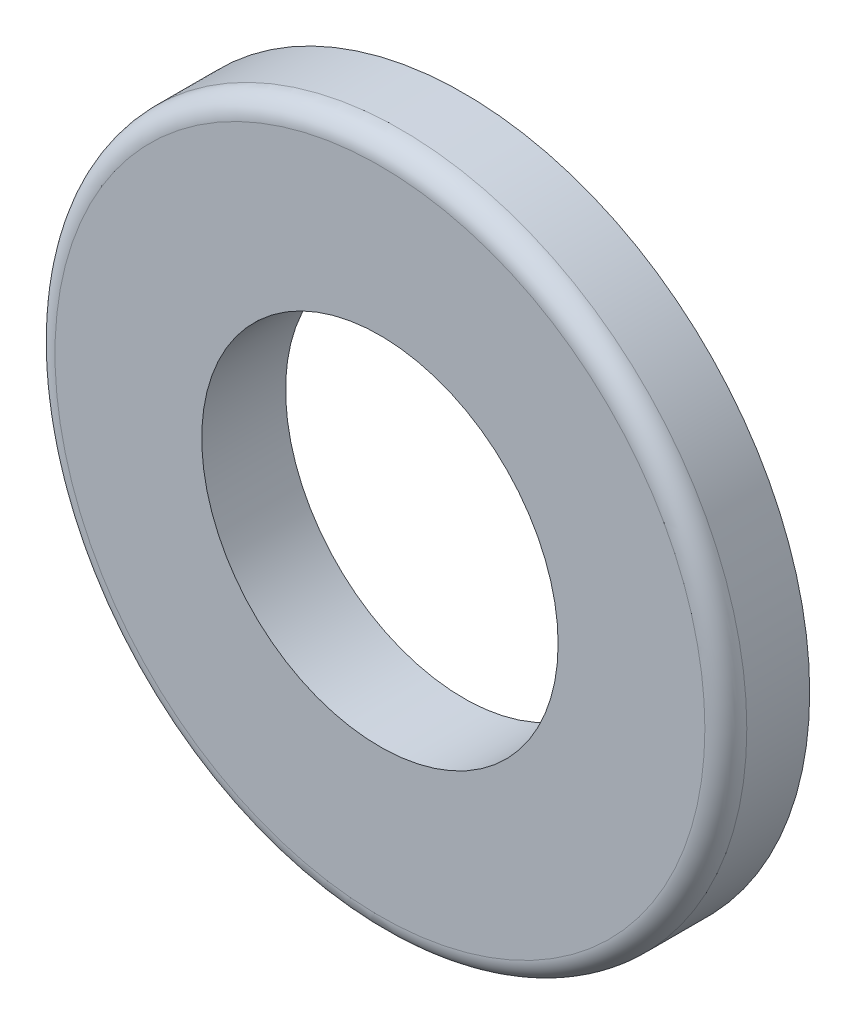
SolidWorks part; units mm, degrees
ref_plane "Front Plane" through (0, 0, 0) normal (0, 0, 1) x (1, 0, 0)
ref_plane "Top Plane" through (0, 0, 0) normal (0, 1, 0) x (1, 0, 0)
ref_plane "Right Plane" through (0, 0, 0) normal (1, 0, 0) x (0, 0, -1)
sketch "Sketch1" plane through (0, 0, 0) normal (0, 0, 1) x (1, 0, 0)
  circle A0 centre (0, 0) radius 8.25
  circle A1 centre (0, 0) radius 4.25
  dimension "Diametro externo" = 16.5
  dimension "Diametro interno" = 8.5
extrude "Boss-Extrude1" add sketch "Sketch1" along normal blind 2
fillet "Fillet1" radius 0.5 1 edges at (8.25, 0, 2)
